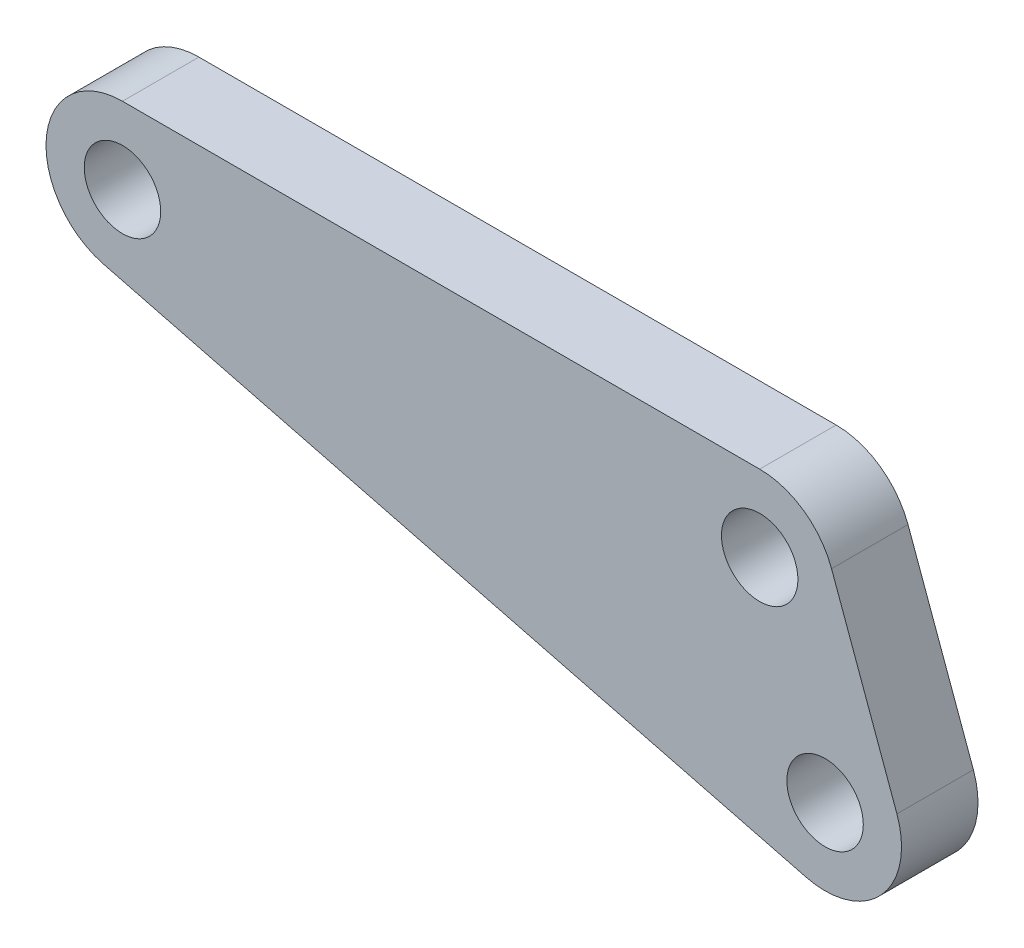
SolidWorks part; units mm, degrees
ref_plane "Front Plane" through (0, 0, 0) normal (0, 0, 1) x (1, 0, 0)
ref_plane "Top Plane" through (0, 0, 0) normal (0, 1, 0) x (1, 0, 0)
ref_plane "Right Plane" through (0, 0, 0) normal (1, 0, 0) x (0, 0, -1)
sketch "Sketch1" plane through (0, 0, 0) normal (0, 0, 1) x (1, 0, 0)
  line L0 (0, 0) -> (-25, 0)
  line L1 (0, 0) -> (2.5652, -7.0477)
  dimension "D1" = 25
  dimension "D2" = 7.5
  dimension "D3" = 110
sketch "Sketch2" plane through (0, 0, 0) normal (0, 0, 1) x (1, 0, 0)
  line L0 (-25, 3) -> (0, 3)
  line L1 (2.8191, 1.0261) -> (5.3842, -6.0216)
  line L2 (1.822, -9.9542) -> (-25.7431, -2.9065)
  circle A0 centre (-25, 0) radius 1.5
  arc A1 (-25, 3) -> (-25.7431, -2.9065) centre (-25, 0) ccw
  circle A2 centre (0, 0) radius 1.5
  arc A3 (2.8191, 1.0261) -> (0, 3) centre (0, 0) ccw
  circle A4 centre (2.5652, -7.0477) radius 1.5
  arc A5 (1.822, -9.9542) -> (5.3842, -6.0216) centre (2.5652, -7.0477) ccw
  dimension "D1" = 3
  dimension "D2" = 6
  dimension "D3" = 3
  dimension "D4" = 6
  dimension "D5" = 3
  dimension "D6" = 6
extrude "Boss-Extrude1" add sketch "Sketch2" along normal blind 3
